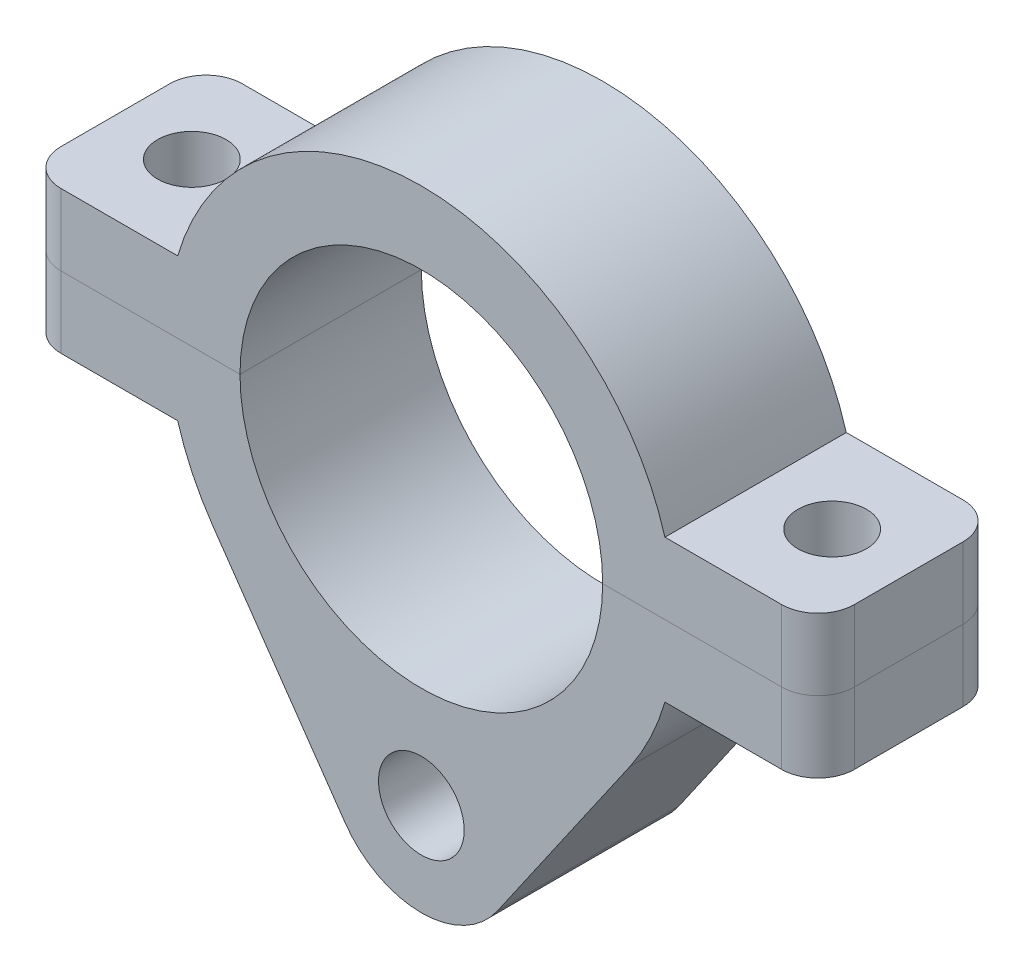
SolidWorks part; units mm, degrees
ref_plane "Front Plane" through (0, 0, 0) normal (0, 0, 1) x (1, 0, 0)
ref_plane "Top Plane" through (0, 0, 0) normal (0, 1, 0) x (1, 0, 0)
ref_plane "Right Plane" through (0, 0, 0) normal (1, 0, 0) x (0, 0, -1)
sketch "Sketch1" plane through (0, 0, 0) normal (0, 0, 1) x (1, 0, 0)
  line L0 (-5.3436, -23.5128) -> (-14.6168, -10.1231)
  line L1 (14.6168, -10.1231) -> (5.3436, -23.5128)
  line L2 (-27.78, 0) -> (27.78, 0) construction
  line L3 (-27.78, -5) -> (27.78, -5)
  line L4 (-27.78, 5) -> (27.78, 5)
  line L5 (-27.78, -5) -> (-27.78, 5)
  line L6 (27.78, -5) -> (27.78, 5)
  circle A0 centre (0, 0) radius 12.7
  circle A2 centre (0, 0) radius 17.78
  circle A3 centre (0, -19.812) radius 3
  circle A4 centre (0, -19.812) radius 6.5
  point P16 (0, 0)
  point P20 (-17.78, 0)
  dimension "D1" = 25.4
  dimension "D3" = 6
  dimension "D7" = 10
  dimension "D5" = 5
  dimension "D8" = 19.812
  dimension "D2" = 5.08
  dimension "D4" = 3.5
  dimension "D6" = 5
extrude "Boss-Extrude1" add sketch "Sketch1" along normal blind 12.7 contours L4 A2 A0 | A0 L2 A2 L4 | L2 A0 L3 A2 | L2 A2 L3 L6 | A2 L2 L6 L4 | A4 A2 L3 A0 | A4 L1 A2 | A2 A4 A3 | A2 A4 | A4 A2 L0 | L2 L5 L3 A2 | L5 L2 A2 L4 | L2 A2 L3 A0 | A2 L2 A0 L4
sketch "Sketch2" plane through (0, -5, 0) normal (0, -1, 0) x (1, 0, 0)
  line L0 (-27.78, 0) -> (-17.0625, 12.7)
  line L1 (0, -55) -> (0, 55) construction
  circle A0 centre (-22.4212, 6.35) radius 2
  circle A1 centre (22.4212, 6.35) radius 2
  circle A2 centre (-22.4212, 6.35) radius 3
  dimension "D1" = 4
  dimension "D2" = 6
hole_wizard "M4 Clearance Hole1" positions "Sketch3" profile "Sketch4" hole size "M4" standard "ANSI Metric" end condition through all
sketch "Sketch3" plane through (0, -5, 0) normal (0, -1, 0) x (-1, 0, 0)
  point P0 (-22.4212, -6.35)
  point P3 (22.4212, -6.35)
sketch "Sketch4" plane through (22.4212, -5, 6.35) normal (1, 0, 0) x (0, 0, -1)
  line L0 (0, 0) -> (0, 22.78)
  line L1 (0, 22.78) -> (2.4, 22.78)
  line L2 (2.4, 22.78) -> (2.4, 0)
  line L5 (2.4, 0) -> (0, 0)
  line L11 (0, -6.35) -> (0, 107.95) construction
  dimension "Thru Hole Dia." = 4.8
  dimension "Thru Hole Depth" = 22.78
fillet "Fillet1" radius 2.54 4 edges at (-27.78, 0, 0) (-27.78, 0, 12.7) (27.78, 0, 0) (27.78, 0, 12.7)
ref_plane "Plane1" through (0, 0, 0) normal (0, -1, 0) x (-1, 0, 0)
split "Split1" trim tools "Plane1" bodies to split 102 resulting bodies 103 104
